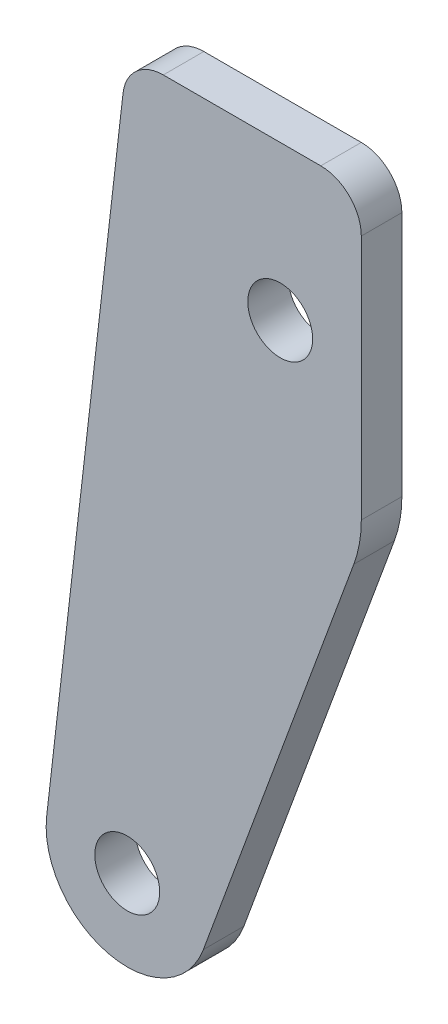
SolidWorks part; units mm, degrees
ref_plane "Płaszczyzna przednia" through (0, 0, 0) normal (0, 0, 1) x (1, 0, 0)
ref_plane "Płaszczyzna górna" through (0, 0, 0) normal (0, 1, 0) x (1, 0, 0)
ref_plane "Płaszczyzna prawa" through (0, 0, 0) normal (1, 0, 0) x (0, 0, -1)
sketch "Szkic1" plane through (0, 0, 0) normal (0, 0, 1) x (1, 0, 0)
  line L3 (17.7361, 175) -> (8.8986, 175)
  line L4 (47.7361, 175) -> (17.7361, 175)
  line L5 (57.7361, 165) -> (57.7361, 104.3439)
  line L6 (57.7361, 99) -> (17.7361, 99)
  line L7 (17.7361, 175) -> (17.7361, 99)
  line L8 (57.7361, 175) -> (17.7361, 99) construction
  line L9 (57.7361, 99) -> (17.7361, 175) construction
  line L10 (-1.036, 166.1418) -> (-19.8692, 2.2837)
  line L11 (55.8908, 93.9848) -> (18.7698, -6.906)
  circle A0 centre (0, 0) radius 8
  circle A1 centre (0, 0) radius 20
  arc A4 (57.7361, 165) -> (47.7361, 175) centre (47.7361, 165) ccw
  arc A5 (8.8986, 175) -> (-1.036, 166.1418) centre (8.8986, 165) ccw
  arc A6 (55.8908, 93.9848) -> (57.7361, 104.3439) centre (27.7361, 104.3439) ccw
  circle A7 centre (37.7361, 137) radius 8
  dimension "D5" = 10
  dimension "D6" = 30
  dimension "D11" = 40
  dimension "D15" = 16
  dimension "D16" = 163.8582
  dimension "D2" = 16
  dimension "D3" = 76
  dimension "D4" = 40
  dimension "D12" = 17.7361
  dimension "D14" = 99
extrude "Dodanie-wyciągnięcie1" add sketch "Szkic1" against normal blind 10
